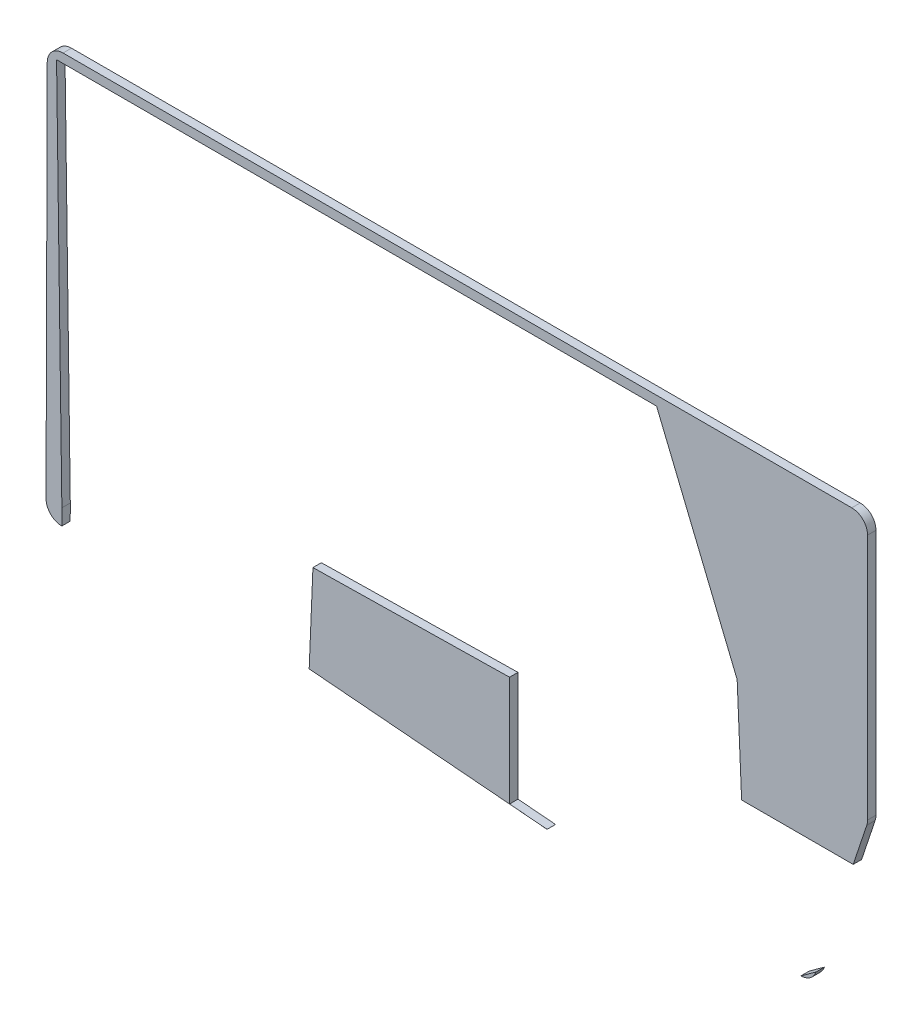
SolidWorks part; units mm, degrees
ref_plane "Front Plane" through (0, 0, 0) normal (0, 0, 1) x (1, 0, 0)
ref_plane "Top Plane" through (0, 0, 0) normal (0, 1, 0) x (1, 0, 0)
ref_plane "Right Plane" through (0, 0, 0) normal (1, 0, 0) x (0, 0, -1)
sketch "Model" plane through (0, 0, 0) normal (0, 0, 1) x (1, 0, 0)
  line L0 (251.9481, -89.4019) -> (101.9885, -89.4981)
  line L1 (98.9904, -92.4885) -> (98.7596, -164.4904)
  line L2 (101.7596, -167.5) -> (148.5292, -167.5)
  line L3 (148.7803, -167.5105) -> (193.7747, -171.2895)
  line L4 (194.0258, -171.3) -> (242.2877, -171.3)
  line L5 (245.1338, -169.2487) -> (254.796, -140.2619)
  line L6 (254.95, -139.3132) -> (254.95, -92.4019)
  line L7 (101.75, -107.75) -> (117.25, -107.75)
  line L8 (117.25, -107.75) -> (117.25, -92.25)
  line L9 (117.25, -92.25) -> (101.75, -92.25)
  line L10 (101.75, -92.25) -> (101.75, -107.75)
  line L11 (120.75, -107.75) -> (136.25, -107.75)
  line L12 (136.25, -107.75) -> (136.25, -92.25)
  line L13 (136.25, -92.25) -> (120.75, -92.25)
  line L14 (120.75, -92.25) -> (120.75, -107.75)
  line L15 (139.75, -107.75) -> (155.25, -107.75)
  line L16 (155.25, -107.75) -> (155.25, -92.25)
  line L17 (155.25, -92.25) -> (139.75, -92.25)
  line L18 (139.75, -92.25) -> (139.75, -107.75)
  line L19 (158.75, -107.75) -> (174.25, -107.75)
  line L20 (174.25, -107.75) -> (174.25, -92.25)
  line L21 (174.25, -92.25) -> (158.75, -92.25)
  line L22 (158.75, -92.25) -> (158.75, -107.75)
  line L23 (177.75, -107.75) -> (193.25, -107.75)
  line L24 (193.25, -107.75) -> (193.25, -92.25)
  line L25 (193.25, -92.25) -> (177.75, -92.25)
  line L26 (177.75, -92.25) -> (177.75, -107.75)
  line L27 (196.75, -107.75) -> (212.25, -107.75)
  line L28 (212.25, -107.75) -> (212.25, -92.25)
  line L29 (212.25, -92.25) -> (196.75, -92.25)
  line L30 (196.75, -92.25) -> (196.75, -107.75)
  line L31 (104.125, -126.75) -> (119.625, -126.75)
  line L32 (119.625, -126.75) -> (119.625, -111.25)
  line L33 (119.625, -111.25) -> (104.125, -111.25)
  line L34 (104.125, -111.25) -> (104.125, -126.75)
  line L35 (125.5, -126.75) -> (141, -126.75)
  line L36 (141, -126.75) -> (141, -111.25)
  line L37 (141, -111.25) -> (125.5, -111.25)
  line L38 (125.5, -111.25) -> (125.5, -126.75)
  line L39 (144.5, -126.75) -> (160, -126.75)
  line L40 (160, -126.75) -> (160, -111.25)
  line L41 (160, -111.25) -> (144.5, -111.25)
  line L42 (144.5, -111.25) -> (144.5, -126.75)
  line L43 (163.5, -126.75) -> (179, -126.75)
  line L44 (179, -126.75) -> (179, -111.25)
  line L45 (179, -111.25) -> (163.5, -111.25)
  line L46 (163.5, -111.25) -> (163.5, -126.75)
  line L47 (182.5, -126.75) -> (198, -126.75)
  line L48 (198, -126.75) -> (198, -111.25)
  line L49 (198, -111.25) -> (182.5, -111.25)
  line L50 (182.5, -111.25) -> (182.5, -126.75)
  line L51 (201.5, -126.75) -> (217, -126.75)
  line L52 (217, -126.75) -> (217, -111.25)
  line L53 (217, -111.25) -> (201.5, -111.25)
  line L54 (201.5, -111.25) -> (201.5, -126.75)
  line L55 (108.875, -145.75) -> (124.375, -145.75)
  line L56 (124.375, -145.75) -> (124.375, -130.25)
  line L57 (124.375, -130.25) -> (108.875, -130.25)
  line L58 (108.875, -130.25) -> (108.875, -145.75)
  line L59 (135, -145.75) -> (150.5, -145.75)
  line L60 (150.5, -145.75) -> (150.5, -130.25)
  line L61 (150.5, -130.25) -> (135, -130.25)
  line L62 (135, -130.25) -> (135, -145.75)
  line L63 (154, -145.75) -> (169.5, -145.75)
  line L64 (169.5, -145.75) -> (169.5, -130.25)
  line L65 (169.5, -130.25) -> (154, -130.25)
  line L66 (154, -130.25) -> (154, -145.75)
  line L67 (173, -145.75) -> (188.5, -145.75)
  line L68 (188.5, -145.75) -> (188.5, -130.25)
  line L69 (188.5, -130.25) -> (173, -130.25)
  line L70 (173, -130.25) -> (173, -145.75)
  line L71 (192, -145.75) -> (207.5, -145.75)
  line L72 (207.5, -145.75) -> (207.5, -130.25)
  line L73 (207.5, -130.25) -> (192, -130.25)
  line L74 (192, -130.25) -> (192, -145.75)
  line L75 (211, -145.75) -> (226.5, -145.75)
  line L76 (226.5, -145.75) -> (226.5, -130.25)
  line L77 (226.5, -130.25) -> (211, -130.25)
  line L78 (211, -130.25) -> (211, -145.75)
  line L79 (104.125, -164.75) -> (119.625, -164.75)
  line L80 (119.625, -164.75) -> (119.625, -149.25)
  line L81 (119.625, -149.25) -> (104.125, -149.25)
  line L82 (104.125, -149.25) -> (104.125, -164.75)
  line L83 (127.78, -164.75) -> (143.28, -164.75)
  line L84 (143.28, -164.75) -> (143.28, -149.25)
  line L85 (143.28, -149.25) -> (127.78, -149.25)
  line L86 (127.78, -149.25) -> (127.78, -164.75)
  line L87 (192.45, -168.55) -> (207.95, -168.55)
  line L88 (207.95, -168.55) -> (207.95, -153.05)
  line L89 (207.95, -153.05) -> (192.45, -153.05)
  line L90 (192.45, -153.05) -> (192.45, -168.55)
  line L91 (221.45, -168.55) -> (236.95, -168.55)
  line L92 (236.95, -168.55) -> (236.95, -153.05)
  line L93 (236.95, -153.05) -> (221.45, -153.05)
  line L94 (221.45, -153.05) -> (221.45, -168.55)
  arc A0 (101.9885, -89.4981) -> (98.9904, -92.4885) centre (101.9904, -92.4981) ccw
  arc A1 (98.7596, -164.4904) -> (101.7596, -167.5) centre (101.7596, -164.5) ccw
  arc A2 (148.7803, -167.5105) -> (148.5292, -167.5) centre (148.5292, -170.5) ccw
  arc A3 (193.7747, -171.2895) -> (194.0258, -171.3) centre (194.0258, -168.3) ccw
  arc A4 (242.2877, -171.3) -> (245.1338, -169.2487) centre (242.2877, -168.3) ccw
  arc A5 (254.796, -140.2619) -> (254.95, -139.3132) centre (251.95, -139.3132) ccw
  arc A6 (254.95, -92.4019) -> (251.9481, -89.4019) centre (251.95, -92.4019) ccw
  circle A7 centre (154.53, -151.3) radius 2.5
  circle A8 centre (181.2, -156.05) radius 2.5
  circle A9 centre (217.8, -94.3) radius 2.5
  circle A10 centre (103.325, -138) radius 2.5
  circle A11 centre (232.05, -138) radius 2.5
  circle A12 centre (122.8, -111.4) radius 2.5
  circle A13 centre (154.53, -151.3) radius 1
  circle A14 centre (181.2, -156.05) radius 1
  circle A15 centre (217.8, -94.3) radius 1
  circle A16 centre (103.325, -138) radius 1
  circle A17 centre (232.05, -138) radius 1
  circle A18 centre (122.8, -111.4) radius 1
extrude "Boss-Extrude1" add sketch "Model" along normal blind 1.6 contours L4 A4 L5 A5 L6 A6 L0 A0 L1 A1 L2 A2 L3 A3
sketch "Sketch2" plane through (0, 0, 1.6) normal (0, 0, 1) x (1, 0, 0)
  line L0 (100.7609, -91.2114) -> (214.8363, -91.2114)
  line L7 (214.8363, -91.2114) -> (230.1585, -128.5742)
  line L8 (230.1585, -128.5742) -> (231.0077, -147.984)
  line L9 (231.0077, -147.984) -> (252.2312, -147.984)
  line L10 (148.7912, -167.5053) -> (149.5046, -150.4628)
  line L11 (149.5046, -150.4628) -> (186.8888, -149.8248)
  line L12 (186.8888, -149.8248) -> (186.8888, -170.705)
  line L13 (148.7912, -167.5053) -> (186.8888, -170.705)
  line L14 (101.7705, -128.5742) -> (100.7609, -91.2114)
  line L15 (101.7705, -128.5742) -> (101.7705, -164.4948)
  point P0 (101.7609, -92.2448)
  point P1 (214.8363, -91.2114)
  point P2 (230.1585, -128.5742)
  point P3 (231.0077, -147.984)
  point P4 (252.2312, -147.984)
  point P5 (186.8888, -149.8248)
  point P6 (149.5046, -150.4628)
  point P7 (186.8888, -170.705)
  point P8 (101.7705, -164.4948)
  point P15 (100.7609, -91.2114)
  point P16 (148.7912, -167.5053)
  point P19 (101.7705, -128.5742)
  line B0 (251.959, -89.3967) -> (101.9994, -89.4929)
  line B1 (99.0013, -92.4832) -> (98.7706, -164.4852)
  line B2 (108.8859, -130.2448) -> (108.8859, -145.7448)
  line B3 (108.8859, -145.7448) -> (124.3859, -145.7448)
  line B4 (119.6359, -149.2448) -> (104.1359, -149.2448)
  line B5 (104.1359, -111.2448) -> (104.1359, -126.7448)
  line B6 (119.6359, -164.7448) -> (119.6359, -149.2448)
  line B7 (127.7909, -149.2448) -> (127.7909, -164.7448)
  line B8 (101.7705, -167.4948) -> (148.5402, -167.4948)
  arc B9 (98.7706, -164.4852) -> (101.7705, -167.4948) centre (101.7705, -164.4948) ccw
  circle B10 centre (103.3359, -137.9948) radius 2.5
  circle B11 centre (103.3359, -137.9948) radius 1
  line B12 (143.2909, -164.7448) -> (143.2909, -149.2448)
  line B13 (104.1359, -149.2448) -> (104.1359, -164.7448)
  line B14 (101.7609, -107.7448) -> (117.2609, -107.7448)
  arc B15 (101.9994, -89.4929) -> (99.0013, -92.4832) centre (102.0013, -92.4929) ccw
  line B16 (155.2609, -92.2448) -> (139.7609, -92.2448)
  line B17 (174.2609, -92.2448) -> (158.7609, -92.2448)
  line B18 (177.7609, -92.2448) -> (177.7609, -107.7448)
  line B19 (212.2609, -107.7448) -> (212.2609, -92.2448)
  line B20 (196.7609, -92.2448) -> (196.7609, -107.7448)
  line B21 (158.7609, -92.2448) -> (158.7609, -107.7448)
  line B22 (155.2609, -107.7448) -> (155.2609, -92.2448)
  line B23 (139.7609, -92.2448) -> (139.7609, -107.7448)
  line B24 (136.2609, -107.7448) -> (136.2609, -92.2448)
  line B25 (120.7609, -92.2448) -> (120.7609, -107.7448)
  line B26 (117.2609, -107.7448) -> (117.2609, -92.2448)
  line B27 (119.6359, -111.2448) -> (104.1359, -111.2448)
  line B28 (104.1359, -126.7448) -> (119.6359, -126.7448)
  line B29 (124.3859, -130.2448) -> (108.8859, -130.2448)
  line B30 (150.5109, -130.2448) -> (135.0109, -130.2448)
  line B31 (144.5109, -126.7448) -> (160.0109, -126.7448)
  line B32 (160.0109, -126.7448) -> (160.0109, -111.2448)
  line B33 (158.7609, -107.7448) -> (174.2609, -107.7448)
  line B34 (136.2609, -92.2448) -> (120.7609, -92.2448)
  line B35 (117.2609, -92.2448) -> (101.7609, -92.2448)
  line B36 (193.2609, -107.7448) -> (193.2609, -92.2448)
  line B37 (196.7609, -107.7448) -> (212.2609, -107.7448)
  line B38 (174.2609, -107.7448) -> (174.2609, -92.2448)
  line B39 (104.1359, -164.7448) -> (119.6359, -164.7448)
  circle B40 centre (217.8109, -94.2948) radius 2.5
  line B41 (245.1447, -169.2435) -> (254.807, -140.2566)
  arc B42 (242.2986, -171.2948) -> (245.1447, -169.2435) centre (242.2986, -168.2948) ccw
  line B43 (194.0367, -171.2948) -> (242.2986, -171.2948)
  line B44 (148.7912, -167.5053) -> (193.7856, -171.2843)
  circle B45 centre (154.5409, -151.2948) radius 2.5
  line B46 (177.7609, -107.7448) -> (193.2609, -107.7448)
  line B47 (198.0109, -111.2448) -> (182.5109, -111.2448)
  line B48 (182.5109, -126.7448) -> (198.0109, -126.7448)
  line B49 (207.5109, -130.2448) -> (192.0109, -130.2448)
  line B50 (192.0109, -130.2448) -> (192.0109, -145.7448)
  line B51 (188.5109, -145.7448) -> (188.5109, -130.2448)
  line B52 (173.0109, -130.2448) -> (173.0109, -145.7448)
  line B53 (169.5109, -145.7448) -> (169.5109, -130.2448)
  line B54 (144.5109, -111.2448) -> (144.5109, -126.7448)
  line B55 (141.0109, -126.7448) -> (141.0109, -111.2448)
  line B56 (135.0109, -145.7448) -> (150.5109, -145.7448)
  line B57 (169.5109, -130.2448) -> (154.0109, -130.2448)
  line B58 (163.5109, -126.7448) -> (179.0109, -126.7448)
  line B59 (139.7609, -107.7448) -> (155.2609, -107.7448)
  line B60 (127.7909, -164.7448) -> (143.2909, -164.7448)
  line B61 (192.4609, -153.0448) -> (192.4609, -168.5448)
  line B62 (207.9609, -168.5448) -> (207.9609, -153.0448)
  line B63 (154.0109, -145.7448) -> (169.5109, -145.7448)
  line B64 (154.0109, -130.2448) -> (154.0109, -145.7448)
  line B65 (150.5109, -145.7448) -> (150.5109, -130.2448)
  line B66 (125.5109, -126.7448) -> (141.0109, -126.7448)
  line B67 (221.4609, -153.0448) -> (221.4609, -168.5448)
  line B68 (192.4609, -168.5448) -> (207.9609, -168.5448)
  line B69 (143.2909, -149.2448) -> (127.7909, -149.2448)
  line B70 (124.3859, -145.7448) -> (124.3859, -130.2448)
  line B71 (119.6359, -126.7448) -> (119.6359, -111.2448)
sketch_block_instance "realBoard-2"
sketch_block "realBoard"
sketch "Sketch3" plane through (0, 0, 1.6) normal (0, 0, 1) x (1, 0, 0)
  line L0 (100.7609, -91.2114) -> (214.8363, -91.2114)
  line L1 (214.8363, -91.2114) -> (230.1585, -128.5742)
  line L2 (230.1585, -128.5742) -> (231.0077, -147.984)
  line L3 (231.0077, -147.984) -> (252.2312, -147.984)
  line L4 (252.2312, -147.984) -> (245.1338, -169.2487)
  line L5 (245.1338, -169.2487) -> (242.2877, -171.3)
  line L6 (242.2877, -171.3) -> (194.0258, -171.3)
  line L7 (194.0258, -171.3) -> (186.8888, -170.705)
  line L8 (186.8888, -170.705) -> (186.8888, -149.8248)
  line L9 (186.8888, -149.8248) -> (149.5046, -150.4628)
  line L10 (149.5046, -150.4628) -> (148.7912, -167.5053)
  line L11 (148.7912, -167.5053) -> (101.7596, -167.5)
  line L12 (101.7596, -167.5) -> (101.7705, -164.4948)
  line L13 (101.7705, -164.4948) -> (100.7609, -91.2114)
extrude "Cut-Extrude1" cut sketch "Sketch3" against normal through all
